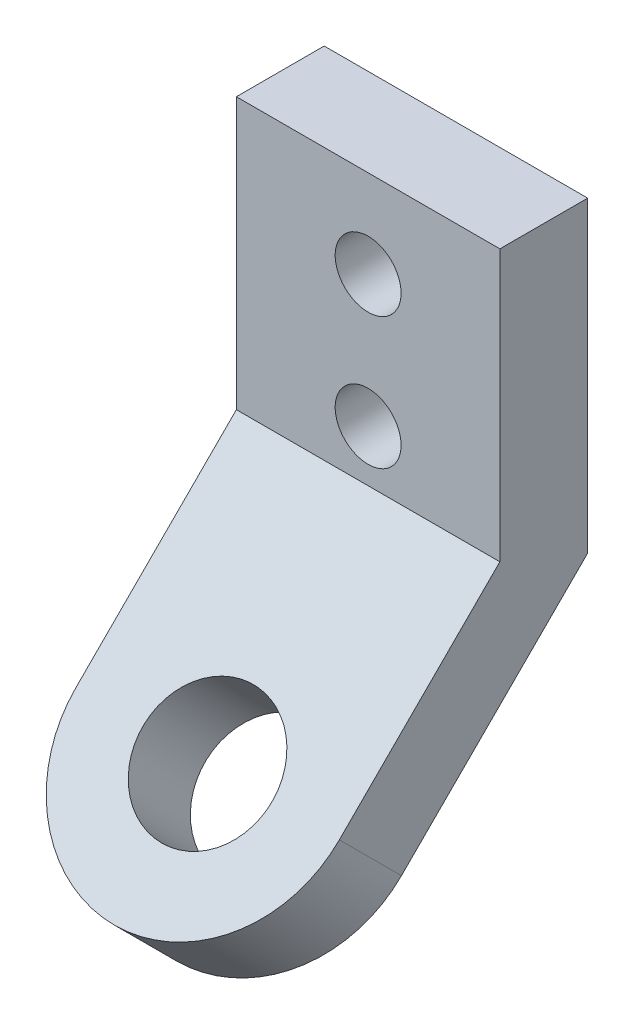
SolidWorks part; units mm, degrees
ref_plane "Front Plane" through (0, 0, 0) normal (1, 0, 0) x (0, 1, 0)
ref_plane "Top Plane" through (0, 0, 0) normal (0, 0, 1) x (0, 1, 0)
ref_plane "Right Plane" through (0, 0, 0) normal (0, 1, 0) x (-1, 0, 0)
sketch "Sketch2" plane through (0, 0, 0) normal (1, 0, 0) x (0, 1, 0)
  line L0 (0, 0) -> (177.8, 0)
  line L1 (177.8, 0) -> (177.8, 50.8)
  line L2 (177.8, 50.8) -> (21.042, 50.8)
  line L3 (21.042, 50.8) -> (-125.6953, 197.5374)
  line L4 (-125.6953, 197.5374) -> (-161.6164, 161.6164)
  line L5 (-161.6164, 161.6164) -> (0, 0)
  dimension "D1" = 50.8
  dimension "D2" = 177.8
  dimension "D3" = 45
  dimension "D4" = 207.518
  dimension "D5" = 50.8
extrude "Boss-Extrude1" add sketch "Sketch2" along normal blind 76.2 contours L5 L0 L1 L2 L3 L4
sketch "Sketch3" plane through (0, 35.921, 35.921) normal (0, 0.7071, 0.7071) x (-1, 0, 0)
  line L0 (0, 21.042) -> (0, 228.56) construction
  line L1 (-76.2, 228.56) -> (0, 228.56) construction
  line L2 (-76.2, 21.042) -> (-76.2, 228.56) construction
  line L3 (-76.2, 21.042) -> (-76.2, 228.56)
  line L4 (-76.2, 228.56) -> (0, 228.56)
  circle A0 centre (0, 152.36) radius 37.465
  circle A1 centre (0, 152.36) radius 76.2
  line M3 (0, 21.042) -> (0, 228.56)
  line M4 (0, 228.56) -> (-76.2, 228.56)
  line M5 (-76.2, 228.56) -> (-76.2, 21.042)
  dimension "D1" = 74.93
extrude "Cut-Extrude1" cut sketch "Sketch3" against normal through all contours A1 M4 M5 | A0 M3
sketch "Sketch4" plane through (0, 0, 50.8) normal (0, 0, 1) x (1, 0, 0)
  line L0 (0, 177.8) -> (0, 21.042) construction
  line L1 (76.2, 177.8) -> (0, 177.8) construction
  circle A0 centre (0, 127) radius 19.05
  circle A1 centre (0, 50.8) radius 19.05
  dimension "D1" = 38.1
  dimension "D2" = 50.8
  dimension "D3" = 76.2
extrude "Cut-Extrude2" cut sketch "Sketch4" against normal through all
mirror "Mirror1" about plane through (0, 0, 0) normal (1, 0, 0) of bodies 103
